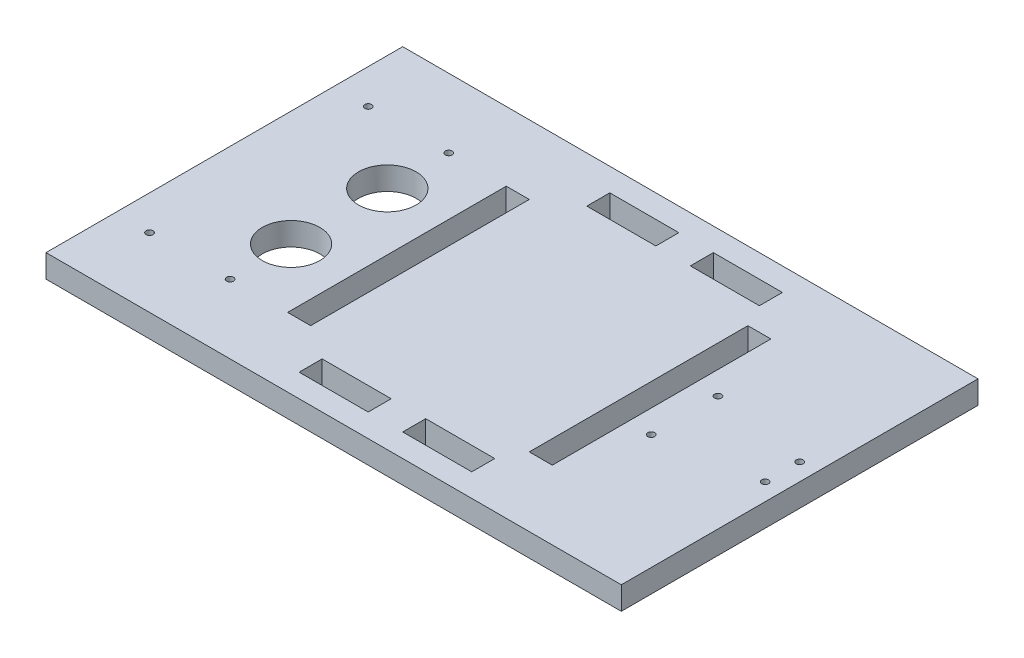
SolidWorks part; units mm, degrees
ref_plane "Front Plane" through (0, 0, 0) normal (0, 0, 1) x (1, 0, 0)
ref_plane "Top Plane" through (0, 0, 0) normal (0, 1, 0) x (1, 0, 0)
ref_plane "Right Plane" through (0, 0, 0) normal (1, 0, 0) x (0, 0, -1)
sketch "Sketch4" plane through (0, 0, 0) normal (0, 1, 0) x (1, 0, 0)
  line L1 (-125, -77.5) -> (125, -77.5)
  line L2 (-125, -77.5) -> (-125, 77.5)
  line L3 (-125, 77.5) -> (125, 77.5)
  line L4 (125, -77.5) -> (125, 77.5)
  line L5 (-125, -77.5) -> (125, 77.5) construction
  line L6 (-125, 77.5) -> (125, -77.5) construction
  point P0 (0, 0)
  dimension "D1" = 250
  dimension "D2" = 155
extrude "Boss-Extrude2" add sketch "Sketch4" along normal blind 10
sketch "Sketch5" plane through (0, 0, 0) normal (0, -1, 0) x (1, 0, 0)
  line L0 (-125, 77.5) -> (125, 77.5) construction
  line L1 (-125, -77.5) -> (-125, 77.5) construction
  circle A0 centre (-110, 47.5) radius 1.5
  dimension "D1" = 3
  dimension "D2" = 30
  dimension "D3" = 15
extrude "Cut-Extrude1" cut sketch "Sketch5" against normal blind 10
mirror "Mirror1" about plane through (0, 0, 0) normal (0, 0, 1) of "Cut-Extrude1"
sketch "Sketch6" plane through (0, 0, 0) normal (0, -1, 0) x (1, 0, 0)
  line L0 (125, 77.5) -> (125, -77.5) construction
  line L1 (-125, 77.5) -> (125, 77.5) construction
  circle A0 centre (75, 14.5) radius 1.5
  dimension "D1" = 50
  dimension "D2" = 63
extrude "Cut-Extrude2" cut sketch "Sketch6" against normal through all both and the other way through all
mirror "Mirror2" about plane through (0, 0, 0) normal (0, 0, 1) of "Cut-Extrude2"
extrude "Cut-Extrude4" cut sketch "Sketch8" against normal through all both and the other way through all
sketch "Sketch8" plane through (-47.5232, 19.5, 165.0878) normal (0, 1, 0) x (1, 0, 0)
  circle A0 centre (-27.4768, 144.0878) radius 12.5
  circle A1 centre (-27.4768, 185.9122) radius 12.5
sketch "Sketch10" plane through (0, 0, 0) normal (0, -1, 0) x (-1, 0, 0)
  circle A0 centre (75, -47.5) radius 1.5
  circle A1 centre (75, -21) radius 12.5 construction
  dimension "D1" = 26.5
  dimension "D2" = 0
extrude "Cut-Extrude5" cut sketch "Sketch10" against normal through all both and the other way through all
mirror "Mirror3" about plane through (0, 0, 0) normal (0, 0, 1) of "Cut-Extrude5"
sketch "Sketch11" plane through (0, 0, 0) normal (0, -1, 0) x (1, 0, 0)
  line L0 (-125, 77.5) -> (125, 77.5) construction
  line L1 (-25, 67.5) -> (5, 67.5)
  line L2 (-25, 67.5) -> (-25, 57.5)
  line L3 (-25, 57.5) -> (5, 57.5)
  line L4 (5, 67.5) -> (5, 57.5)
  line L5 (-25, 67.5) -> (5, 57.5) construction
  line L6 (-25, 57.5) -> (5, 67.5) construction
  line L7 (-125, -77.5) -> (-125, 77.5) construction
  point P0 (-10, 62.5)
  dimension "D1" = 10
  dimension "D2" = 30
  dimension "D3" = 10
  dimension "D4" = 100
extrude "Cut-Extrude6" cut sketch "Sketch11" against normal through all both and the other way through all
sketch "Sketch12" plane through (0, 0, 0) normal (0, -1, 0) x (-1, 0, 0)
  line L0 (-125, -77.5) -> (-125, 77.5) construction
  line L1 (-20, -67.5) -> (-50, -67.5)
  line L2 (-20, -67.5) -> (-20, -57.5)
  line L3 (-20, -57.5) -> (-50, -57.5)
  line L4 (-50, -67.5) -> (-50, -57.5)
  line L5 (-20, -67.5) -> (-50, -57.5) construction
  line L6 (-20, -57.5) -> (-50, -67.5) construction
  line L7 (125, -77.5) -> (-125, -77.5) construction
  point P0 (-35, -62.5)
  dimension "D1" = 75
  dimension "D2" = 30
  dimension "D3" = 10
  dimension "D4" = 10
extrude "Cut-Extrude7" cut sketch "Sketch12" against normal through all both and the other way through all
mirror "Mirror4" about plane through (0, 0, 0) normal (0, 0, 1) of "Cut-Extrude6", "Cut-Extrude7"
sketch "Sketch14" plane through (0, 0, 0) normal (0, -1, 0) x (1, 0, 0)
  line L0 (125, 77.5) -> (125, -77.5) construction
  circle A0 centre (117.5, 7.5) radius 1.5
  dimension "D1" = 3
  dimension "D2" = 7.5
  dimension "D3" = 7.5
extrude "Cut-Extrude8" cut sketch "Sketch14" against normal through all both and the other way through all
mirror "Mirror5" about plane through (0, 0, 0) normal (0, 0, 1) of "Cut-Extrude8"
extrude "Cut-Extrude9" cut sketch "Sketch16" against normal blind 10
sketch "Sketch16" plane through (-47.5232, 10, 165.0878) normal (0, 1, 0) x (1, 0, 0)
  line L1 (112.5232, 117.5878) -> (102.5232, 117.5878)
  line L2 (112.5232, 117.5878) -> (112.5232, 212.5878)
  line L3 (112.5232, 212.5878) -> (102.5232, 212.5878)
  line L4 (102.5232, 117.5878) -> (102.5232, 212.5878)
  line L8 (7.5232, 117.5878) -> (-2.4768, 117.5878)
  line L9 (7.5232, 117.5878) -> (7.5232, 212.5878)
  line L10 (7.5232, 212.5878) -> (-2.4768, 212.5878)
  line L11 (-2.4768, 117.5878) -> (-2.4768, 212.5878)
